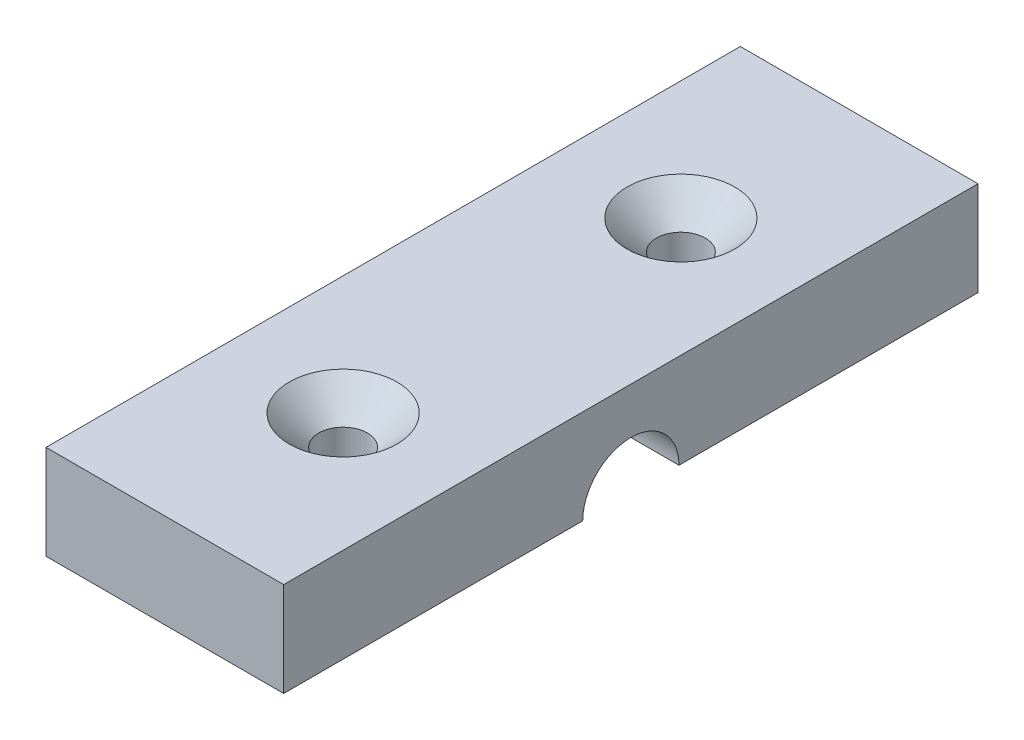
SolidWorks part; units mm, degrees
ref_plane "Top Plane" through (0, 0, 0) normal (0, 0, 1) x (1, 0, 0)
ref_plane "Front Plane" through (0, 0, 0) normal (0, 1, 0) x (1, 0, 0)
ref_plane "Right Plane" through (0, 0, 0) normal (1, 0, 0) x (0, 0, -1)
sketch "Sketch1" plane through (0, -110.0687, 0) normal (0, 1, 0) x (1, 0, 0)
  line L1 (88.3339, -91.8373) -> (68.3339, -91.8373)
  line L2 (88.3339, -91.8373) -> (88.3339, -33.4173)
  line L3 (88.3339, -33.4173) -> (68.3339, -33.4173)
  line L4 (68.3339, -91.8373) -> (68.3339, -33.4173)
  circle A0 centre (78.3339, -76.8373) radius 2.05
  circle A1 centre (78.3339, -48.4173) radius 2.05
  circle A2 centre (78.3339, -76.8373) radius 1.625 construction
  circle A3 centre (78.3339, -48.4173) radius 1.625 construction
  point P20 (78.3339, -91.8373)
  dimension "D2" = 4.1
extrude "Boss-Extrude1" add sketch "Sketch1" along normal blind 7.9375
extrude "Cut-Extrude1" cut sketch "Sketch2" against normal blind 15
sketch "Sketch2" plane through (88.3339, -1.5875, 4.9363) normal (1, 0, 0) x (0, 0, -1)
  circle A0 centre (-57.691, -108.4812) radius 4.05
chamfer "Chamfer1" distance 2.48 angle 45 2 edges at (78.3339, -102.1312, 50.4673) (78.3339, -102.1312, 78.8873)
